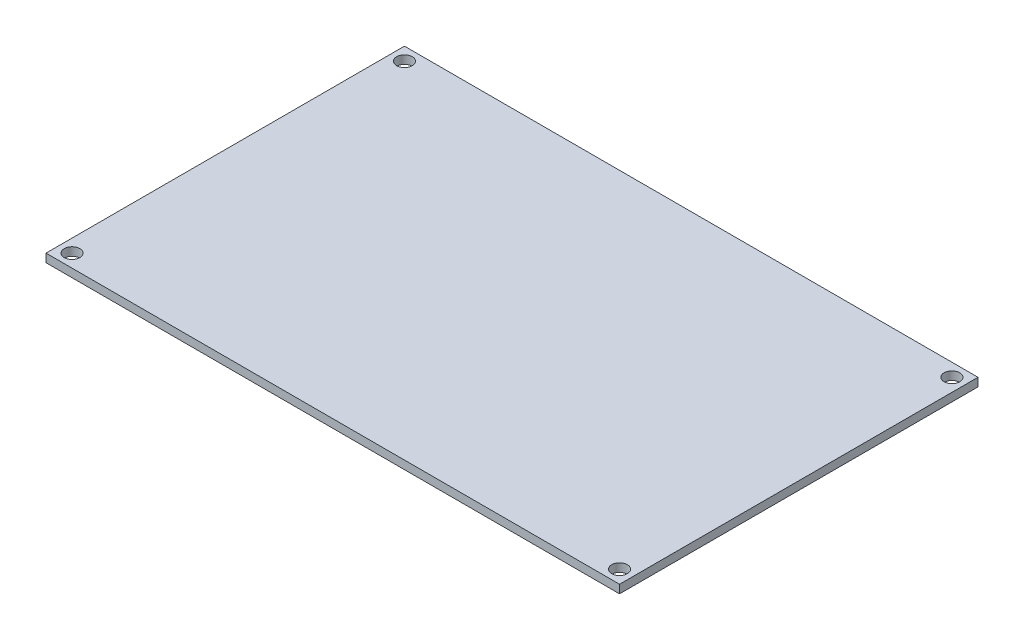
SolidWorks part; units mm, degrees
ref_plane "Front Plane" through (0, 0, 0) normal (0, 0, 1) x (1, 0, 0)
ref_plane "Top Plane" through (0, 0, 0) normal (0, 1, 0) x (1, 0, 0)
ref_plane "Right Plane" through (0, 0, 0) normal (1, 0, 0) x (0, 0, -1)
sketch "Sketch1" plane through (0, 0, 0) normal (0, 1, 0) x (1, 0, 0)
  line L0 (-55, 0) -> (55, 0) construction
  line L1 (-55, -34.375) -> (55, -34.375)
  line L2 (-55, -34.375) -> (-55, 34.375)
  line L3 (-55, 34.375) -> (55, 34.375)
  line L4 (55, -34.375) -> (55, 34.375)
  line L5 (-55, -34.375) -> (55, 34.375) construction
  line L6 (-55, 34.375) -> (55, -34.375) construction
  line L7 (0, -55) -> (0, 55) construction
  circle A0 centre (-52.5, 31.875) radius 1.5
  circle A1 centre (-52.5, -31.875) radius 1.5
  circle A2 centre (52.5, -31.875) radius 1.5
  circle A3 centre (52.5, 31.875) radius 1.5
  point P0 (0, 0)
  dimension "D3" = 3
  dimension "D1" = 110
  dimension "D2" = 68.75
  dimension "D4" = 2.5
  dimension "D5" = 2.5
extrude "Boss-Extrude1" add sketch "Sketch1" along normal blind 1.6
